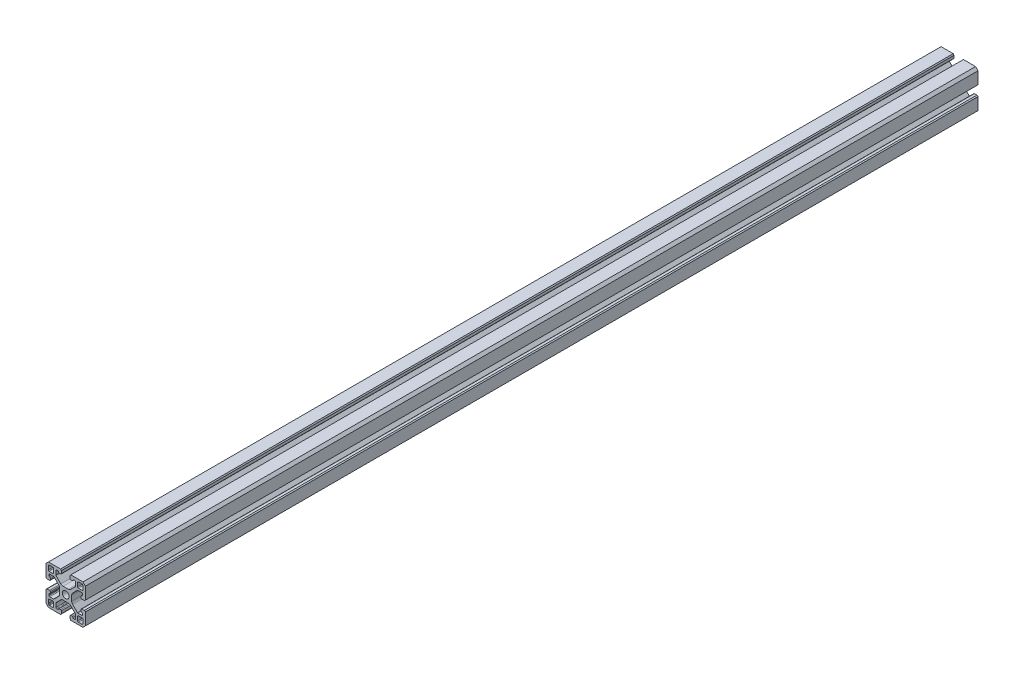
SolidWorks part; units mm, degrees
material "6063-T6"
ref_plane "Front Plane" through (0, 0, 0) normal (0, 0, 1) x (1, 0, 0)
ref_plane "Top Plane" through (0, 0, 0) normal (0, 1, 0) x (1, 0, 0)
ref_plane "Right Plane" through (0, 0, 0) normal (1, 0, 0) x (0, 0, -1)
sketch "Sketch1" plane through (0, 0, 0) normal (0, 0, 1) x (-1, 0, 0)
  line L0 (19.05, 0) -> (-19.05, 0) construction
  line L1 (0, -19.05) -> (0, 19.05) construction
  line L2 (-19.05, 4.9276) -> (-19.05, 16.6878)
  line L3 (-18.044, 4.1656) -> (-19.05, 4.9276)
  line L4 (-15.6692, 4.1656) -> (-18.044, 4.1656)
  line L5 (-14.9297, 6.2238) -> (-14.9074, 4.9409)
  line L6 (-16.256, 8.763) -> (-16.256, 7.7216)
  line L7 (-16.256, -7.7216) -> (-16.256, -8.763)
  line L8 (-14.9074, -4.9409) -> (-14.9297, -6.2238)
  line L9 (-18.044, -4.1656) -> (-15.6692, -4.1656)
  line L10 (-19.05, -4.9276) -> (-18.044, -4.1656)
  line L11 (-19.05, -16.6878) -> (-19.05, -4.9276)
  line L26 (-16.8656, 12.319) -> (-16.8656, 15.6829)
  line L27 (-16.6424, 16.2217) -> (-16.2217, 16.6424)
  line L28 (-15.6829, 16.8656) -> (-12.319, 16.8656)
  line L29 (-11.557, 16.1036) -> (-11.557, 12.319)
  line L30 (-12.319, 11.557) -> (-16.1036, 11.557)
  line L31 (-6.7001, -4.7245) -> (-11.2775, -9.3018)
  line L32 (-11.8163, -9.525) -> (-15.494, -9.525)
  line L34 (-15.494, 9.525) -> (-11.8163, 9.525)
  line L35 (-11.2775, 9.3018) -> (-6.7001, 4.7245)
  line L36 (-5.8074, 2.5692) -> (-5.8074, -2.5692)
  line L37 (-16.1036, -11.557) -> (-12.319, -11.557)
  line L38 (-11.557, -12.319) -> (-11.557, -16.1036)
  line L39 (-12.319, -16.8656) -> (-15.6829, -16.8656)
  line L40 (-16.2217, -16.6424) -> (-16.6424, -16.2217)
  line L41 (-16.8656, -15.6829) -> (-16.8656, -12.319)
  line L42 (15.6829, -16.8656) -> (12.319, -16.8656)
  line L43 (11.557, -16.1036) -> (11.557, -12.319)
  line L44 (12.319, -11.557) -> (16.1036, -11.557)
  line L45 (16.8656, -12.319) -> (16.8656, -15.6829)
  line L46 (16.6424, -16.2217) -> (16.2217, -16.6424)
  line L47 (11.557, 12.319) -> (11.557, 16.1036)
  line L48 (12.319, 16.8656) -> (15.6829, 16.8656)
  line L49 (16.2217, 16.6424) -> (16.6424, 16.2217)
  line L100 (5.8074, -2.5692) -> (5.8074, 2.5692)
  line L101 (6.7001, 4.7245) -> (11.2775, 9.3018)
  line L102 (11.8163, 9.525) -> (15.494, 9.525)
  line L103 (16.256, 8.763) -> (16.256, 7.7216)
  line L104 (14.9297, 6.2238) -> (14.9074, 4.9409)
  line L105 (15.6692, 4.1656) -> (18.044, 4.1656)
  line L106 (18.044, 4.1656) -> (19.05, 4.9276)
  line L107 (19.05, 4.9276) -> (19.05, 16.6878)
  line L108 (19.05, 16.6878) -> (16.6878, 19.05)
  line L109 (16.6878, 19.05) -> (4.9276, 19.05)
  line L110 (4.9276, 19.05) -> (4.1656, 18.044)
  line L111 (4.1656, 18.044) -> (4.1656, 15.6692)
  line L112 (4.9409, 14.9074) -> (6.2238, 14.9297)
  line L113 (7.7216, 16.256) -> (8.763, 16.256)
  line L114 (9.525, 15.494) -> (9.525, 11.8163)
  line L115 (9.3018, 11.2775) -> (4.7245, 6.7001)
  line L116 (2.5692, 5.8074) -> (-2.5692, 5.8074)
  line L117 (-4.7245, 6.7001) -> (-9.3018, 11.2775)
  line L118 (-9.525, 11.8163) -> (-9.525, 15.494)
  line L119 (-8.763, 16.256) -> (-7.7216, 16.256)
  line L120 (-6.2238, 14.9297) -> (-4.9409, 14.9074)
  line L121 (-4.1656, 15.6692) -> (-4.1656, 18.044)
  line L122 (-4.1656, 18.044) -> (-4.9276, 19.05)
  line L123 (-4.9276, 19.05) -> (-16.6878, 19.05)
  line L124 (-16.6878, 19.05) -> (-19.05, 16.6878)
  line L126 (-19.05, -16.6878) -> (-16.6878, -19.05)
  line L127 (-16.6878, -19.05) -> (-4.9276, -19.05)
  line L128 (-4.9276, -19.05) -> (-4.1656, -18.044)
  line L129 (-4.1656, -18.044) -> (-4.1656, -15.6692)
  line L130 (-4.9409, -14.9074) -> (-6.2238, -14.9297)
  line L131 (-7.7216, -16.256) -> (-8.763, -16.256)
  line L132 (-9.525, -15.494) -> (-9.525, -11.8163)
  line L133 (-9.3018, -11.2775) -> (-4.7245, -6.7001)
  line L134 (-2.5692, -5.8074) -> (2.5692, -5.8074)
  line L135 (4.7245, -6.7001) -> (9.3018, -11.2775)
  line L136 (9.525, -11.8163) -> (9.525, -15.494)
  line L137 (8.763, -16.256) -> (7.7216, -16.256)
  line L138 (6.2238, -14.9297) -> (4.9409, -14.9074)
  line L139 (4.1656, -15.6692) -> (4.1656, -18.044)
  line L140 (4.1656, -18.044) -> (4.9409, -19.05)
  line L141 (4.9409, -19.05) -> (16.6878, -19.05)
  line L142 (16.6878, -19.05) -> (19.05, -16.6878)
  line L143 (19.05, -16.6878) -> (19.05, -4.9276)
  line L144 (19.05, -4.9276) -> (18.044, -4.1656)
  line L145 (18.044, -4.1656) -> (15.6692, -4.1656)
  line L146 (14.9074, -4.9409) -> (14.9297, -6.2238)
  line L147 (16.256, -7.7216) -> (16.256, -8.763)
  line L148 (15.494, -9.525) -> (11.8163, -9.525)
  line L149 (11.2775, -9.3018) -> (6.7001, -4.7245)
  line L150 (16.8656, 15.6829) -> (16.8656, 12.319)
  line L151 (16.1036, 11.557) -> (12.319, 11.557)
  arc A0 (-16.256, 8.763) -> (-15.494, 9.525) centre (-15.494, 8.763) cw
  arc A1 (-14.9074, 4.9409) -> (-15.6692, 4.1656) centre (-15.6692, 4.9276) cw
  arc A2 (-15.5928, 6.966) -> (-14.9297, 6.2238) centre (-15.6916, 6.2105) cw
  arc A3 (-15.5928, 6.966) -> (-16.256, 7.7216) centre (-15.494, 7.7216) cw
  arc A4 (-15.494, -9.525) -> (-16.256, -8.763) centre (-15.494, -8.763) cw
  arc A5 (-16.256, -7.7216) -> (-15.5928, -6.966) centre (-15.494, -7.7216) cw
  arc A6 (-14.9297, -6.2238) -> (-15.5928, -6.966) centre (-15.6916, -6.2105) cw
  arc A7 (-15.6692, -4.1656) -> (-14.9074, -4.9409) centre (-15.6692, -4.9276) cw
  arc A27 (-16.6424, 16.2217) -> (-16.8656, 15.6829) centre (-16.1036, 15.6829) ccw
  arc A28 (-15.6829, 16.8656) -> (-16.2217, 16.6424) centre (-15.6829, 16.1036) ccw
  arc A29 (-11.557, 16.1036) -> (-12.319, 16.8656) centre (-12.319, 16.1036) ccw
  arc A30 (-12.319, 11.557) -> (-11.557, 12.319) centre (-12.319, 12.319) ccw
  arc A31 (-16.8656, 12.319) -> (-16.1036, 11.557) centre (-16.1036, 12.319) ccw
  arc A32 (-11.8163, -9.525) -> (-11.2775, -9.3018) centre (-11.8163, -8.763) ccw
  arc A35 (-11.2775, 9.3018) -> (-11.8163, 9.525) centre (-11.8163, 8.763) ccw
  arc A72 (5.8074, -2.5692) -> (6.7001, -4.7245) centre (8.8554, -2.5692) ccw
  arc A73 (6.7001, 4.7245) -> (5.8074, 2.5692) centre (8.8554, 2.5692) ccw
  arc A74 (11.8163, 9.525) -> (11.2775, 9.3018) centre (11.8163, 8.763) ccw
  arc A75 (16.256, 8.763) -> (15.494, 9.525) centre (15.494, 8.763) ccw
  arc A76 (15.5928, 6.966) -> (16.256, 7.7216) centre (15.494, 7.7216) ccw
  arc A77 (15.5928, 6.966) -> (14.9297, 6.2238) centre (15.6916, 6.2105) ccw
  arc A78 (14.9074, 4.9409) -> (15.6692, 4.1656) centre (15.6692, 4.9276) ccw
  arc A79 (4.1656, 15.6692) -> (4.9409, 14.9074) centre (4.9276, 15.6692) ccw
  arc A80 (6.2238, 14.9297) -> (6.966, 15.5928) centre (6.2105, 15.6916) ccw
  arc A81 (7.7216, 16.256) -> (6.966, 15.5928) centre (7.7216, 15.494) ccw
  arc A82 (9.525, 15.494) -> (8.763, 16.256) centre (8.763, 15.494) ccw
  arc A83 (9.3018, 11.2775) -> (9.525, 11.8163) centre (8.763, 11.8163) ccw
  arc A84 (2.5692, 5.8074) -> (4.7245, 6.7001) centre (2.5692, 8.8554) ccw
  arc A85 (-4.7245, 6.7001) -> (-2.5692, 5.8074) centre (-2.5692, 8.8554) ccw
  arc A86 (-9.525, 11.8163) -> (-9.3018, 11.2775) centre (-8.763, 11.8163) ccw
  arc A87 (-8.763, 16.256) -> (-9.525, 15.494) centre (-8.763, 15.494) ccw
  arc A88 (-6.966, 15.5928) -> (-7.7216, 16.256) centre (-7.7216, 15.494) ccw
  arc A89 (-6.966, 15.5928) -> (-6.2238, 14.9297) centre (-6.2105, 15.6916) ccw
  arc A90 (-4.9409, 14.9074) -> (-4.1656, 15.6692) centre (-4.9276, 15.6692) ccw
  arc A91 (-4.1656, -15.6692) -> (-4.9409, -14.9074) centre (-4.9276, -15.6692) ccw
  arc A92 (-6.2238, -14.9297) -> (-6.966, -15.5928) centre (-6.2105, -15.6916) ccw
  arc A93 (-7.7216, -16.256) -> (-6.966, -15.5928) centre (-7.7216, -15.494) ccw
  arc A94 (-9.525, -15.494) -> (-8.763, -16.256) centre (-8.763, -15.494) ccw
  arc A95 (-9.3018, -11.2775) -> (-9.525, -11.8163) centre (-8.763, -11.8163) ccw
  arc A96 (-2.5692, -5.8074) -> (-4.7245, -6.7001) centre (-2.5692, -8.8554) ccw
  arc A97 (4.7245, -6.7001) -> (2.5692, -5.8074) centre (2.5692, -8.8554) ccw
  arc A98 (9.525, -11.8163) -> (9.3018, -11.2775) centre (8.763, -11.8163) ccw
  arc A99 (8.763, -16.256) -> (9.525, -15.494) centre (8.763, -15.494) ccw
  arc A100 (6.966, -15.5928) -> (7.7216, -16.256) centre (7.7216, -15.494) ccw
  arc A101 (6.966, -15.5928) -> (6.2238, -14.9297) centre (6.2105, -15.6916) ccw
  arc A102 (4.9409, -14.9074) -> (4.1656, -15.6692) centre (4.9276, -15.6692) ccw
  arc A103 (15.6692, -4.1656) -> (14.9074, -4.9409) centre (15.6692, -4.9276) ccw
  arc A104 (14.9297, -6.2238) -> (15.5928, -6.966) centre (15.6916, -6.2105) ccw
  arc A105 (16.256, -7.7216) -> (15.5928, -6.966) centre (15.494, -7.7216) ccw
  arc A106 (15.494, -9.525) -> (16.256, -8.763) centre (15.494, -8.763) ccw
  arc A107 (11.2775, -9.3018) -> (11.8163, -9.525) centre (11.8163, -8.763) ccw
  arc A108 (-5.8074, 2.5692) -> (-6.7001, 4.7245) centre (-8.8554, 2.5692) ccw
  arc A109 (-6.7001, -4.7245) -> (-5.8074, -2.5692) centre (-8.8554, -2.5692) ccw
  arc A110 (-11.557, -12.319) -> (-12.319, -11.557) centre (-12.319, -12.319) ccw
  arc A111 (-12.319, -16.8656) -> (-11.557, -16.1036) centre (-12.319, -16.1036) ccw
  arc A112 (-16.2217, -16.6424) -> (-15.6829, -16.8656) centre (-15.6829, -16.1036) ccw
  arc A113 (-16.8656, -15.6829) -> (-16.6424, -16.2217) centre (-16.1036, -15.6829) ccw
  arc A114 (-16.1036, -11.557) -> (-16.8656, -12.319) centre (-16.1036, -12.319) ccw
  circle A115 centre (0, 0) radius 3.3147
  arc A116 (11.557, -16.1036) -> (12.319, -16.8656) centre (12.319, -16.1036) ccw
  arc A117 (12.319, -11.557) -> (11.557, -12.319) centre (12.319, -12.319) ccw
  arc A118 (16.8656, -12.319) -> (16.1036, -11.557) centre (16.1036, -12.319) ccw
  arc A119 (16.6424, -16.2217) -> (16.8656, -15.6829) centre (16.1036, -15.6829) ccw
  arc A120 (15.6829, -16.8656) -> (16.2217, -16.6424) centre (15.6829, -16.1036) ccw
  arc A121 (12.319, 16.8656) -> (11.557, 16.1036) centre (12.319, 16.1036) ccw
  arc A122 (16.2217, 16.6424) -> (15.6829, 16.8656) centre (15.6829, 16.1036) ccw
  arc A123 (16.8656, 15.6829) -> (16.6424, 16.2217) centre (16.1036, 15.6829) ccw
  arc A124 (16.1036, 11.557) -> (16.8656, 12.319) centre (16.1036, 12.319) ccw
  arc A125 (11.557, 12.319) -> (12.319, 11.557) centre (12.319, 12.319) ccw
  dimension "D1" = 6.6294
  dimension "D2" = 38.1
  dimension "D3" = 38.1
extrude "Boss-Extrude1" add sketch "Sketch1" along normal blind 863.6
